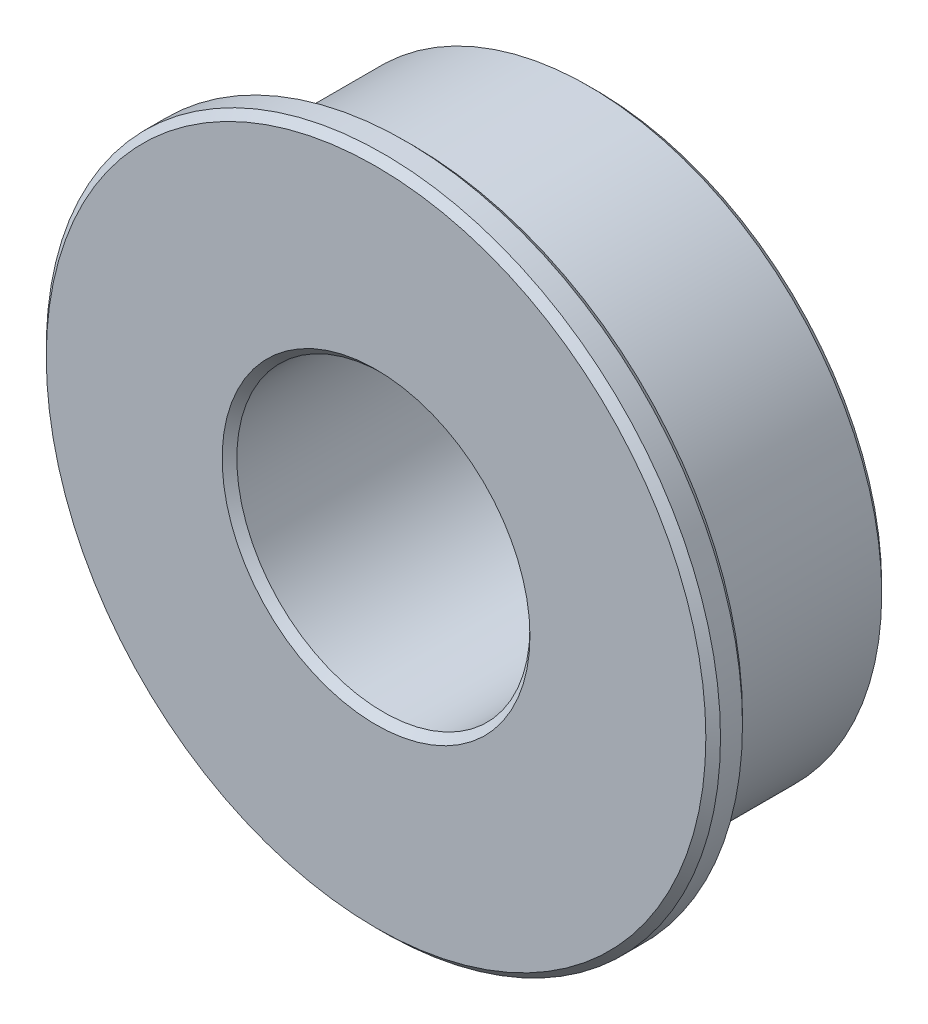
SolidWorks part; units mm, degrees
material "1023 碳钢板 (SS)"
ref_plane "前视基准面" through (0, 0, 0) normal (0, 0, 1) x (1, 0, 0)
ref_plane "上视基准面" through (0, 0, 0) normal (0, 1, 0) x (1, 0, 0)
ref_plane "右视基准面" through (0, 0, 0) normal (1, 0, 0) x (0, 0, -1)
other "Configuration Table"
sketch "草图1" plane through (0, 0, 0) normal (0, 0, 1) x (1, 0, 0)
  circle A0 centre (0, 0) radius 2
  circle A1 centre (0, 0) radius 4
  dimension "D1" = 4
  dimension "D2" = 8
extrude "凸台-拉伸1" add sketch "草图1" along normal blind 3
sketch "草图2" plane through (0, 0, 3) normal (0, 0, 1) x (1, 0, 0)
  circle A0 centre (0, 0) radius 4.6
  circle A1 centre (0, 0) radius 4 construction
  circle A2 centre (0, 0) radius 4
  dimension "D1" = 9.2
extrude "凸台-拉伸2" add sketch "草图2" against normal blind 0.5
chamfer "倒角1" distance 0.1 angle 45 5 edges at (4.6, 0, 3) (4.6, 0, 2.5) (2, 0, 0) (2, 0, 3) (4, 0, 0)
